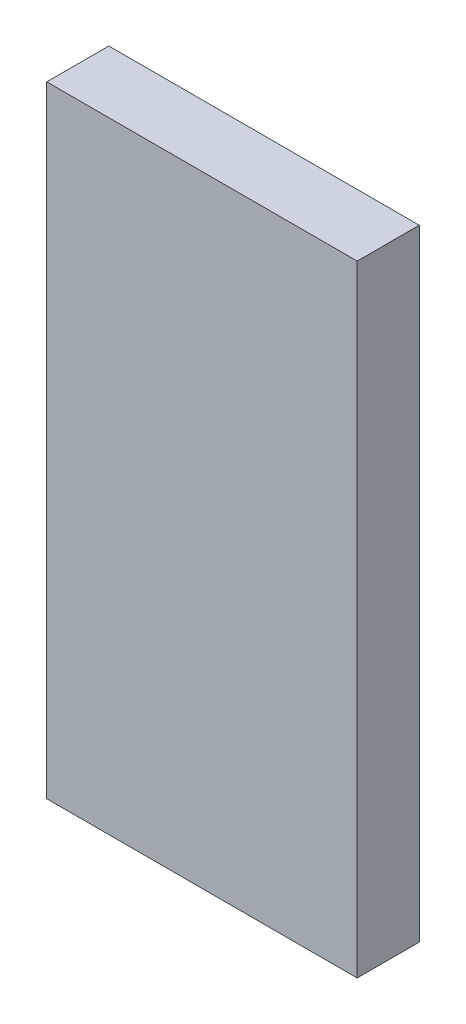
SolidWorks part; units mm, degrees
ref_plane "前基準面" through (0, 0, 0) normal (0, 0, 1) x (1, 0, 0)
ref_plane "上基準面" through (0, 0, 0) normal (0, 1, 0) x (1, 0, 0)
ref_plane "右基準面" through (0, 0, 0) normal (1, 0, 0) x (0, 0, -1)
sketch "草圖1" plane through (0, 0, 0) normal (0, 0, 1) x (1, 0, 0)
  line L1 (0, 0) -> (60, 0)
  line L2 (0, 0) -> (0, 120)
  line L3 (0, 120) -> (60, 120)
  line L4 (60, 0) -> (60, 120)
  dimension "D1" = 60
  dimension "D2" = 120
extrude "填料-伸長1" add sketch "草圖1" along normal blind 12
